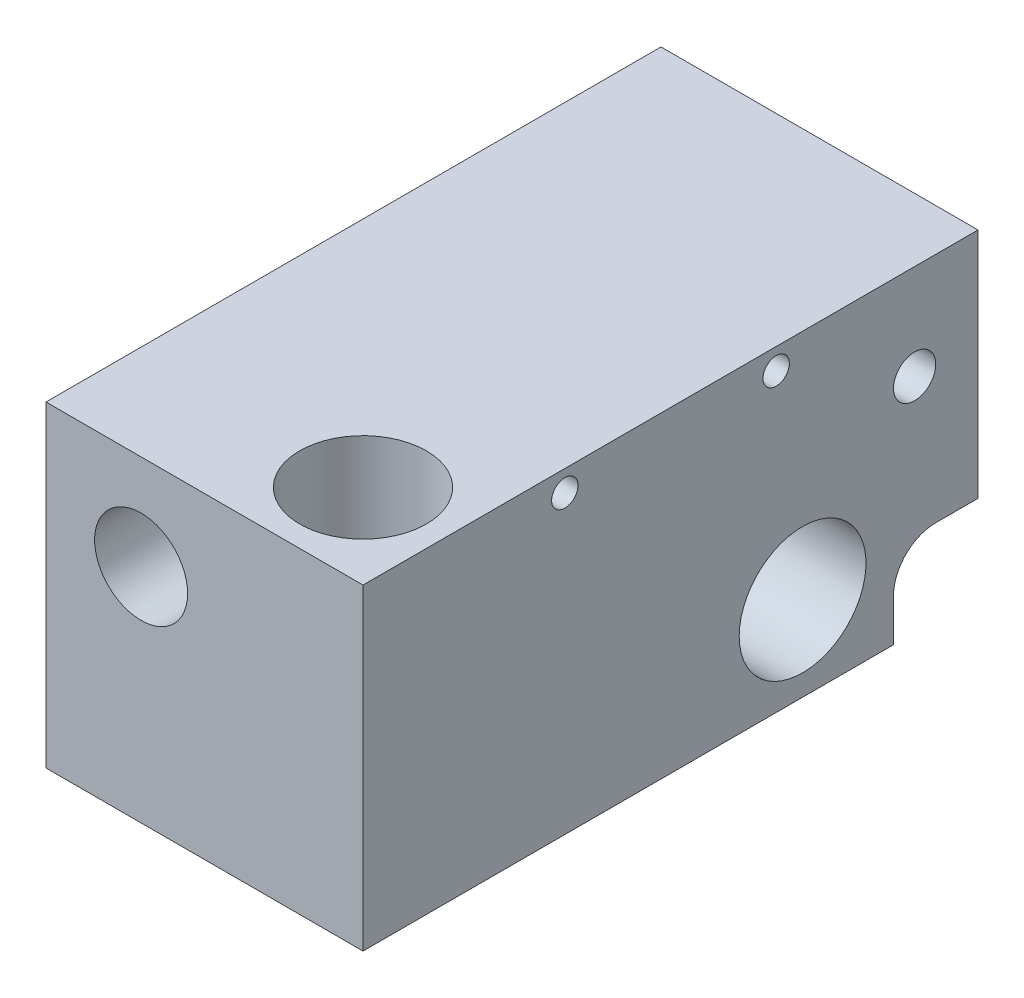
SolidWorks part; units mm, degrees
material "Lega 1060"
ref_plane "Piano frontale" through (0, 0, 0) normal (0, 0, 1) x (1, 0, 0)
ref_plane "Piano superiore" through (0, 0, 0) normal (0, 1, 0) x (1, 0, 0)
ref_plane "Piano destro" through (0, 0, 0) normal (1, 0, 0) x (0, 0, -1)
sketch "Schizzo1" plane through (0, 0, 0) normal (0, 0, 1) x (1, 0, 0)
  line L1 (0, 0) -> (30, 0)
  line L2 (0, 0) -> (0, 30)
  line L3 (0, 30) -> (30, 30)
  line L4 (30, 0) -> (30, 30)
  dimension "D1" = 30
extrude "Estrusione-Estrusione1" add sketch "Schizzo1" along normal blind 58.2
sketch "Schizzo2" plane through (0, 0, 0) normal (0, -1, 0) x (1, 0, 0)
  line L1 (0, 58.2) -> (30, 58.2) construction
  line L3 (30, 58.2) -> (30, 0) construction
  circle A0 centre (22, 50.2) radius 6
  dimension "D1" = 12
  dimension "D3" = 2
  dimension "D2" = 2
extrude "Taglio-Estrusione1" cut sketch "Schizzo2" against normal up to next
ref_point "Punto1"
sketch "Schizzo3" plane through (0, 0, 0) normal (-1, 0, 0) x (0, 0, 1)
  line L0 (50.2, 0) -> (50.2, 8) construction
  line L1 (50.2, 8) -> (16.6, 8) construction
  line L3 (58.2, 0) -> (0, 0) construction
  circle A0 centre (16.6, 8) radius 6
  dimension "D1" = 12
  dimension "D3" = 2
  dimension "D2" = 33.6
extrude "Taglio-Estrusione2" cut sketch "Schizzo3" against normal up to next
sketch "Schizzo5" plane through (0, 0, 0) normal (0, 0, -1) x (-1, 0, 0)
  line L0 (0, 30) -> (-30, 0) construction
  line L1 (0, 30) -> (0, 0) construction
  line L2 (-30, 30) -> (0, 30) construction
  circle A0 centre (-9, 21) radius 7
  dimension "D1" = 14
  dimension "D2" = 9
  dimension "D3" = 9
extrude "Taglio-Estrusione3" cut sketch "Schizzo5" against normal blind 20
hole_wizard "Foro Ø6.0 (6)-1" positions "Schizzo7" profile "Schizzo6" hole size "Ø6.0" standard "ISO" end condition up to next
sketch "Schizzo7" plane through (0, 0, 58.2) normal (0, 0, 1) x (1, 0, 0)
  line L0 (0, 30) -> (30, 0) construction
  line L2 (0, 0) -> (30, 0) construction
  line L3 (30, 0) -> (30, 30) construction
  line L4 (0, 30) -> (0, 0) construction
  line L5 (30, 30) -> (0, 30) construction
  circle A1 centre (9, 21) radius 7 construction
  point P0 (9, 21)
  dimension "D1" = 14
  dimension "D2" = 2
  dimension "D3" = 9
sketch "Schizzo6" plane through (9, 21, 58.2) normal (1, 0, 0) x (0, -1, 0)
  line L0 (0, 0) -> (0, 38.2)
  line L1 (0, 38.2) -> (3, 38.2)
  line L2 (3, 38.2) -> (3, 0)
  line L5 (3, 0) -> (0, 0)
  line L11 (0, -6.35) -> (0, 107.95) construction
  dimension "Thru Hole Dia." = 6
  dimension "Thru Hole Depth" = 38.2
hole_wizard "Foro filettato G1/8-1" positions "Schizzo3D1" profile "Schizzo8" tap size "G1/8" standard "BSI"
sketch3d "Schizzo3D1"
  line L0 (9, 21, 20) -> (9, 21, 58.2) construction
  point P0 (9, 21, 58.2)
sketch "Schizzo8" plane through (9, 21, 58.2) normal (1, 0, 0) x (0, -1, 0)
  line L0 (0, 0) -> (0, 12.6438)
  line L1 (0, 12.6438) -> (4.4, 10)
  line L2 (4.4, 10) -> (4.4, 0)
  line L5 (4.4, 0) -> (0, 0)
  line L10 (0, 12.6438) -> (-4.4, 10) construction
  line L11 (0, -6.35) -> (0, 107.95) construction
  dimension "Tap Drill Dia." = 8.8
  dimension "Tap Drill Depth" = 10
  dimension "Drill Angle" = 118
hole_wizard "Foro filettato M3-1" positions "Schizzo10" profile "Schizzo9" tap size "M3" standard "ISO"
sketch "Schizzo10" plane through (30, 0, 0) normal (1, 0, 0) x (0, 0, -1)
  line L0 (0, 0) -> (0, 30) construction
  line L1 (-6, 21) -> (-10.6716, 21) construction
  line L4 (-58.2, 30) -> (0, 30) construction
  point P0 (-6, 21)
  dimension "D1" = 6
  dimension "D2" = 9
cosmetic thread "Filettatura del foro1" parameters "D2"=3
sketch "Schizzo9" plane through (30, 21, 6) normal (0, 1, 0) x (0, 0, -1)
  line L0 (0, 0) -> (0, 14)
  line L1 (0, 14) -> (1.25, 14)
  line L2 (1.25, 14) -> (1.25, 0)
  line L5 (1.25, 0) -> (0, 0)
  line L11 (0, -6.35) -> (0, 107.95) construction
  dimension "Thru Tap Drill Dia." = 2.5
  dimension "Thru Tap Drill Depth" = 14
hole_wizard "Foro Ø4.0 (4)-2" positions "Schizzo14" profile "Schizzo13" hole size "Ø4.0" standard "ISO"
sketch "Schizzo14" plane through (30, 0, 0) normal (1, 0, 0) x (0, 0, -1)
  point P0 (-6, 21)
sketch "Schizzo13" plane through (30, 21, 6) normal (0, 1, 0) x (0, 0, -1)
  line L0 (0, 0) -> (0, 9.2017)
  line L1 (0, 9.2017) -> (2, 8)
  line L2 (2, 8) -> (2, 0)
  line L5 (2, 0) -> (0, 0)
  line L10 (0, 9.2017) -> (-2, 8) construction
  line L11 (0, -6.35) -> (0, 107.95) construction
  dimension "Hole Dia." = 4
  dimension "Hole Depth" = 8
  dimension "Drill Angle" = 118
sketch "Schizzo20" plane through (0, 0, 0) normal (-1, 0, 0) x (0, 0, 1)
  line L0 (4, 8) -> (0, 8)
  line L1 (0, 0) -> (8, 0) construction
  line L2 (0, 0) -> (0, 8) construction
  line L3 (0, 8) -> (8, 8) construction
  line L4 (8, 0) -> (8, 8) construction
  line L5 (0, 8) -> (0, 0)
  line L6 (0, 0) -> (8, 0)
  line L7 (8, 0) -> (8, 4)
  arc A1 (8, 4) -> (4, 8) centre (4, 4) ccw
  dimension "D1" = 8
  dimension "D2" = 8
  dimension "D3" = 8
extrude "Taglio-Estrusione5" cut sketch "Schizzo20" against normal blind 10
sketch "Schizzo21" plane through (30, 0, 0) normal (1, 0, 0) x (0, 0, -1)
  line L0 (-8, 0) -> (-8, 4) construction
  line L2 (-4, 8) -> (0, 8) construction
  line L3 (0, 8) -> (0, 0) construction
  line L4 (-8, 0) -> (-8, 4)
  line L5 (0, 0) -> (-8, 0)
  line L6 (-4, 8) -> (0, 8)
  line L7 (0, 8) -> (0, 0)
  arc A0 (-4, 8) -> (-8, 4) centre (-4, 4) ccw construction
  arc A1 (-4, 8) -> (-8, 4) centre (-4, 4) ccw
extrude "Taglio-Estrusione6" cut sketch "Schizzo21" against normal blind 10
sketch "Schizzo23" plane through (10, 0, 0) normal (-1, 0, 0) x (0, 0, 1)
  circle A0 centre (3.6, 3.6) radius 1.6
extrude "Taglio-Estrusione7" cut sketch "Schizzo23" against normal up to surface (10 mm away) up to face at (20, 4.1657, 4.1657)
sketch "Schizzo24" plane through (0, 0, 20) normal (0, 0, -1) x (-1, 0, 0)
  circle A0 centre (-9, 21) radius 3
  circle A1 centre (-9, 21) radius 7
extrude "Estrusione-Estrusione2" add sketch "Schizzo24" along normal blind 7
sketch "Schizzo25" plane through (30, 0, 0) normal (1, 0, 0) x (0, 0, -1)
  point P0 (-39.1, 28)
  point P1 (-19.1, 28)
hole_wizard "Foro filettato M3-2" positions "Schizzo3D2" profile "Schizzo27" tap size "M3" standard "ISO"
sketch3d "Schizzo3D2"
  point P0 (30, 28, 39.1)
  point P3 (30, 28, 19.1)
sketch "Schizzo27" plane through (30, 28, 39.1) normal (0, 1, 0) x (0, 0, -1)
  line L0 (0, 0) -> (0, 12.2511)
  line L1 (0, 12.2511) -> (1.25, 11.5)
  line L2 (1.25, 11.5) -> (1.25, 0)
  line L5 (1.25, 0) -> (0, 0)
  line L10 (0, 12.2511) -> (-1.25, 11.5) construction
  line L11 (0, -6.35) -> (0, 107.95) construction
  dimension "Tap Drill Dia." = 2.5
  dimension "Tap Drill Depth" = 11.5
  dimension "Drill Angle" = 118
cosmetic thread "Filettatura del foro2" parameters "D1"=10, "D2"=3
cosmetic thread "Filettatura del foro3" parameters "D1"=10, "D2"=3
